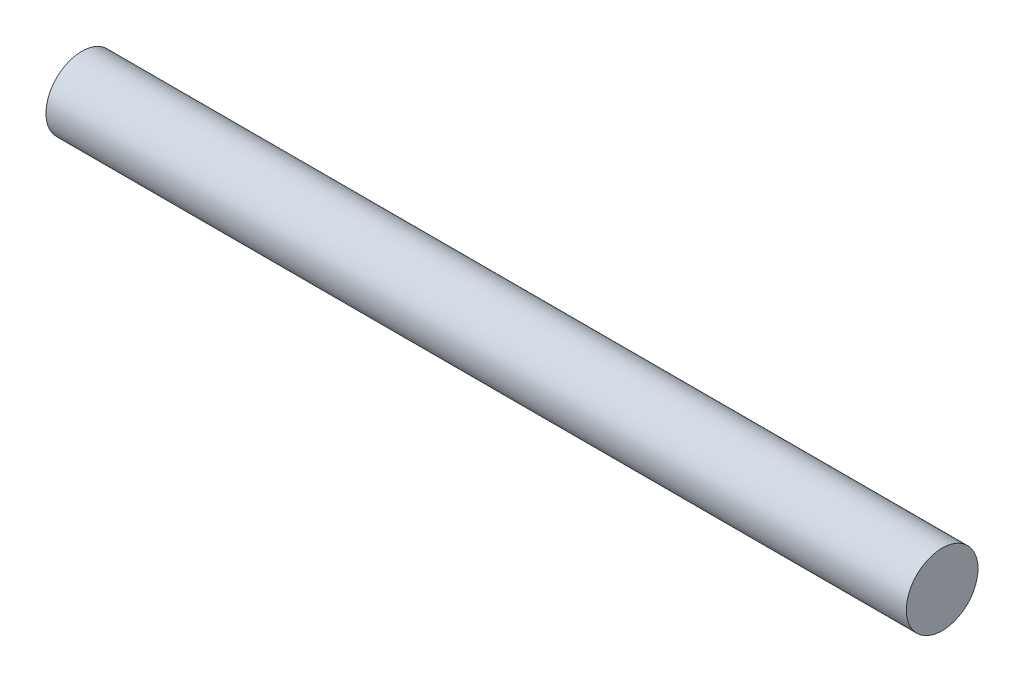
SolidWorks part; units mm, degrees
material "Stainless Steel (ferritic)"
ref_plane "Front Plane" through (0, 0, 0) normal (0, 0, 1) x (1, 0, 0)
ref_plane "Top Plane" through (0, 0, 0) normal (0, 1, 0) x (1, 0, 0)
ref_plane "Right Plane" through (0, 0, 0) normal (1, 0, 0) x (0, 0, -1)
sketch "Sketch2" plane through (0, 0, 0) normal (1, 0, 0) x (0, 0, -1)
  circle A0 centre (0, 0) radius 1.5
  dimension "D1" = 3
extrude "Boss-Extrude1" add sketch "Sketch2" along normal blind 36
